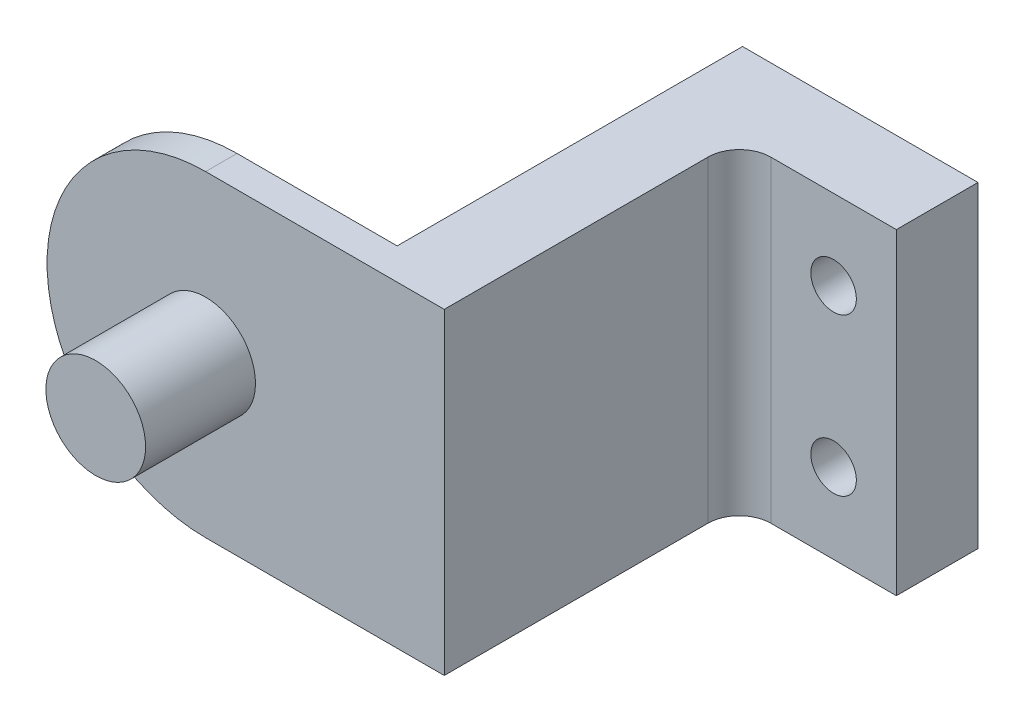
SolidWorks part; units mm, degrees
material "ABS"
ref_plane "Front" through (0, 0, 0) normal (0, 0, 1) x (1, 0, 0)
ref_plane "Top" through (0, 0, 0) normal (0, 1, 0) x (1, 0, 0)
ref_plane "Right" through (0, 0, 0) normal (1, 0, 0) x (0, 0, -1)
sketch "Esquisse1" plane through (0, 0, 0) normal (0, 0, 1) x (1, 0, 0)
  line L1 (-2.5, 10.1) -> (2.5, 10.1)
  line L2 (-2.5, 10.1) -> (-2.5, -10.1)
  line L3 (-2.5, -10.1) -> (2.5, -10.1)
  line L4 (2.5, 10.1) -> (2.5, -10.1)
  line L5 (-2.5, 10.1) -> (2.5, -10.1) construction
  line L6 (-2.5, -10.1) -> (2.5, 10.1) construction
  point P0 (0, 0)
  dimension "D1" = 5
  dimension "D2" = 20.2
extrude "Boss.-Extru.1" add sketch "Esquisse1" along normal blind 22
sketch "Esquisse2" plane through (0, 0, 22) normal (0, 0, 1) x (1, 0, 0)
  line L0 (-2.5, -10.1) -> (2.5, -10.1) construction
  line L1 (2.5, 10.1) -> (-12.7, 10.1)
  line L2 (2.5, 10.1) -> (2.5, -10.1)
  line L3 (2.5, -10.1) -> (-12.7, -10.1)
  arc A0 (-12.7, 10.1) -> (-12.7, -10.1) centre (-12.7, 0) ccw
  dimension "D1" = 15.2
extrude "Boss.-Extru.2" add sketch "Esquisse2" along normal blind 2
sketch "Esquisse3" plane through (0, 0, 24) normal (0, 0, 1) x (1, 0, 0)
  circle A0 centre (-12.7, 0) radius 3.175
  arc A1 (-12.7, 10.1) -> (-12.7, -10.1) centre (-12.7, 0) ccw construction
  dimension "D1" = 6.35
extrude "Boss.-Extru.3" add sketch "Esquisse3" along normal blind 7
sketch "Sketch1" plane through (2.5, 0, 0) normal (1, 0, 0) x (0, 0, -1)
  line L0 (-24, 10.1) -> (0, 10.1) construction
  line L1 (0, -10.1) -> (-5.2, -10.1)
  line L2 (0, -10.1) -> (0, 10.1)
  line L3 (0, 10.1) -> (-5.2, 10.1)
  line L4 (-5.2, -10.1) -> (-5.2, 10.1)
  dimension "D1" = 5.2
extrude "Boss-Extrude1" add sketch "Sketch1" along normal blind 10
sketch "Sketch2" plane through (0, 0, 0) normal (0, 0, -1) x (-1, 0, 0)
  circle A0 centre (-8.5, -5) radius 1.45
  circle A1 centre (-8.5, 5) radius 1.45
  dimension "D4" = 2.9
  dimension "D1" = 4
  dimension "D2" = 5.1
  dimension "D3" = 2
extrude "Cut-Extrude1" cut sketch "Sketch2" against normal through all
fillet "Fillet1" radius 2 1 edges at (2.5, 0, 5.2)
